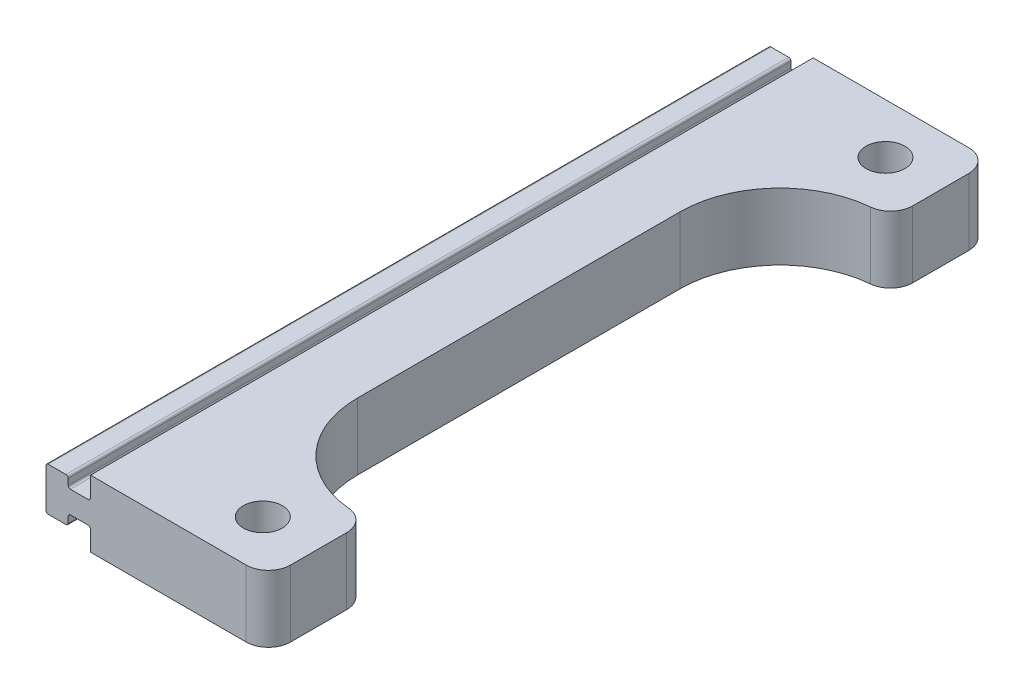
SolidWorks part; units mm, degrees
ref_plane "Alzado" through (0, 0, 0) normal (0, 0, 1) x (1, 0, 0)
ref_plane "Planta" through (0, 0, 0) normal (0, 1, 0) x (1, 0, 0)
ref_plane "Vista lateral" through (0, 0, 0) normal (1, 0, 0) x (0, 0, -1)
sketch "Croquis1" plane through (0, 0, 0) normal (0, 1, 0) x (1, 0, 0)
  line L1 (-5, 32.5) -> (5, 32.5)
  line L2 (-5, 32.5) -> (-5, -32.5)
  line L3 (-5, -32.5) -> (5, -32.5)
  line L4 (5, 14.5) -> (5, -14.5)
  line L5 (-5, 32.5) -> (0, 0) construction
  line L6 (-5, -32.5) -> (5, 32.5) construction
  line L7 (5, -32.5) -> (15, -32.5)
  line L9 (14, -23.5) -> (15, -23.5)
  line L10 (15, -32.5) -> (15, -23.5)
  line L11 (5, 32.5) -> (15, 32.5)
  line L13 (14, 23.5) -> (15, 23.5)
  line L14 (15, 32.5) -> (15, 23.5)
  arc A0 (14, 23.5) -> (5, 14.5) centre (14, 14.5) ccw
  arc A1 (14, -23.5) -> (5, -14.5) centre (14, -14.5) cw
  point P0 (0, 0)
  dimension "D7" = 9
  dimension "D1" = 65
  dimension "D2" = 10
  dimension "D3" = 10
  dimension "D4" = 10
  dimension "D5" = 9
  dimension "D6" = 9
extrude "Saliente-Extruir1" add sketch "Croquis1" along normal blind 6
sketch "Croquis2" plane through (0, 6, 0) normal (0, 1, 0) x (1, 0, 0)
  line L0 (5, -23.5) -> (15, -32.5) construction
  line L1 (0, 0) -> (12.4607, 0) construction
  circle A0 centre (10, -28) radius 1.75
  circle A1 centre (10, 28) radius 1.75
  dimension "D1" = 3.5
extrude "Cortar-Extruir1" cut sketch "Croquis2" against normal blind 6
sketch "Croquis4" plane through (0, 0, 32.5) normal (0, 0, 1) x (1, 0, 0)
  line L0 (-5, 0) -> (-1, 0)
  line L1 (-5, 0) -> (15, 0) construction
  line L2 (-1, 0) -> (-1, 2)
  line L3 (-1, 2) -> (-3, 2)
  line L4 (-3, 2) -> (-3, 1.05)
  line L5 (-3, 1.05) -> (-5, 1.05)
  line L6 (-5, 6) -> (-5, 0) construction
  line L7 (-5, 3) -> (-0.3385, 3) construction
  line L8 (-5, 6) -> (-1, 6)
  line L9 (-1, 6) -> (-1, 4)
  line L10 (-1, 4) -> (-3, 4)
  line L11 (-3, 4) -> (-3, 4.95)
  line L12 (-3, 4.95) -> (-5, 4.95)
  line L13 (-5, 0) -> (-5, 1.05)
  line L14 (-5, 4.95) -> (-5, 6)
  dimension "D1" = 4
  dimension "D2" = 2
  dimension "D3" = 2
  dimension "D4" = 0.95
  dimension "D5" = 1.05
extrude "Cortar-Extruir2" cut sketch "Croquis4" against normal through all
fillet "Redondeo1" radius 0.2 8 edges at (-3, 1.05, 0) (-5, 1.05, 0) (-5, 4.95, 0) (-3, 4.95, 0) (-1, 2, 0) (-1, 4, 0) (-3, 2, 0) (-3, 4, 0)
fillet "Redondeo2" radius 2 4 edges at (15, 3, 32.5) (15, 3, 23.5) (15, 3, -23.5) (15, 3, -32.5)
